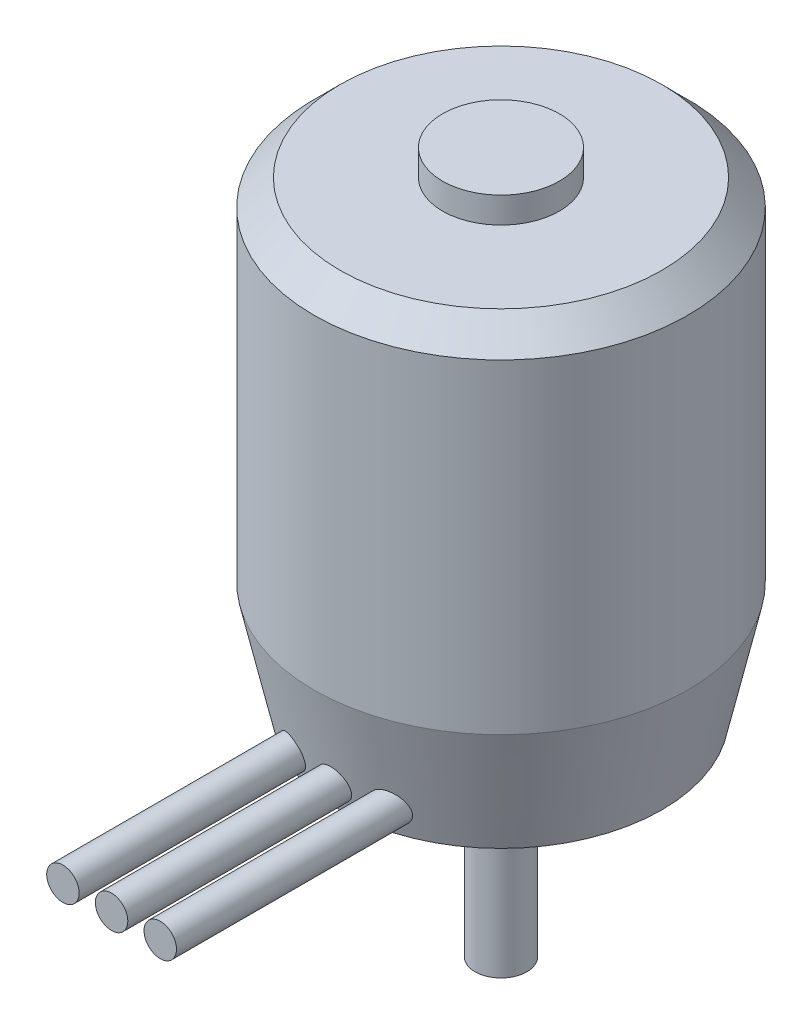
SolidWorks part; units mm, degrees
ref_plane "Front Plane" through (0, 0, 0) normal (0, 0, 1) x (1, 0, 0)
ref_plane "Top Plane" through (0, 0, 0) normal (0, 1, 0) x (1, 0, 0)
ref_plane "Right Plane" through (0, 0, 0) normal (1, 0, 0) x (0, 0, -1)
other "Center of Mass"
sketch "Sketch1" plane through (0, 0, 0) normal (0, 0, 1) x (1, 0, 0)
  line L0 (0, 0) -> (0, -80.2628) construction
  line L5 (14.4, -45.0247) -> (14.4, -20.0247)
  line L6 (0, -36.0247) -> (14.4, -18.0247) construction
  line L7 (0, -56.5968) -> (3.9, -58.3688) construction
  line L8 (0, -16.0247) -> (4.5, -16.0247)
  line L11 (4.5, -16.0247) -> (4.5, -18.0247)
  line L12 (0, -17.0247) -> (4.5, -18.0247) construction
  line L13 (0, -17.0247) -> (4.5, -16.0247) construction
  line L14 (12.4, -18.0247) -> (14.4, -20.0247)
  line L16 (0, -70.0247) -> (2, -70.0247)
  line L19 (2, -70.0247) -> (2, -58.3688)
  line L20 (0, -62.0247) -> (2, -54.0247) construction
  line L21 (0, -70.0247) -> (0, -16.0247)
  line L25 (3.9, -55.8247) -> (3.9, -58.3688)
  line L27 (0, -56.5968) -> (3.9, -54.8247) construction
  line L28 (2.9, -54.8247) -> (3.9, -55.8247)
  line L29 (12.4, -54.0247) -> (14.4, -45.0247)
  line L31 (4.5, -18.0247) -> (12.4, -18.0247)
  line L32 (2, -54.8247) -> (2.9, -54.8247)
  line L33 (2, -54.0247) -> (12.4, -54.0247)
  line L35 (2, -54.8247) -> (2, -54.0247)
  line L36 (2, -58.3688) -> (3.9, -58.3688)
  line L37 (0, -36.0247) -> (14.4, -54.0247) construction
  line L38 (0, -62.0247) -> (2, -70.0247) construction
  point P3 (0, -36.0247)
  point P8 (0, -17.0247)
  point P17 (0, -62.0247)
  point P23 (0, -56.5968)
  dimension "D6" = 54
  dimension "D15" = 2
  dimension "D16" = 25
ref_axis "Axis1" through (0, 0, 0) along (0, -1, 0)
revolve "Revolve2" add sketch "Sketch1" angle 360 about axis through (0, 0, 0) along (0, -1, 0)
sketch "Sketch2" plane through (0, -54.0247, 0) normal (0, -1, 0) x (1, 0, 0)
  line L0 (0, 0) -> (6.7175, 6.7175) construction
  line L1 (0, 0) -> (0, 9.5) construction
  line L2 (0, 0) -> (5.6569, -5.6569) construction
  circle A0 centre (0, 0) radius 8 construction
  circle A1 centre (0, 0) radius 9.5 construction
  circle A2 centre (6.7175, 6.7175) radius 1.5
  circle A3 centre (5.6569, -5.6569) radius 1.5
  circle A4 centre (-6.7175, -6.7175) radius 1.5
  circle A5 centre (-5.6569, 5.6569) radius 1.5
  point P13 (0, 0)
  point P16 (0, 0)
  dimension "D1" = 19
  dimension "D2" = 16
  dimension "D3" = 45
  dimension "D5" = 3
  dimension "D6" = 3
  dimension "D8" = 2
  dimension "D4" = 90
  dimension "D7" = 2
extrude "Cut-Extrude1" cut sketch "Sketch2" against normal blind 6
ref_plane "Plane1" through (0, 0, 10) normal (0, 0, 1) x (1, 0, 0)
sketch "Sketch3" plane through (0, 0, 10) normal (0, 0, 1) x (1, 0, 0)
  line L0 (0, -16.0247) -> (0, -72.7849) construction
  line L1 (4.5, -16.0247) -> (-4.5, -16.0247) construction
  line L2 (-18.1899, -52.0247) -> (18.1899, -52.0247) construction
  line L3 (-12.4, -54.0247) -> (12.4, -54.0247) construction
  circle A0 centre (0, -52.0247) radius 1.25
  circle A1 centre (3.75, -52.0247) radius 1.25
  circle A2 centre (-3.75, -52.0247) radius 1.25
  dimension "D1" = 2.5
  dimension "D2" = 3.75
  dimension "D3" = 3.75
  dimension "D4" = 2
extrude "Boss-Extrude1" add sketch "Sketch3" along normal blind 20
